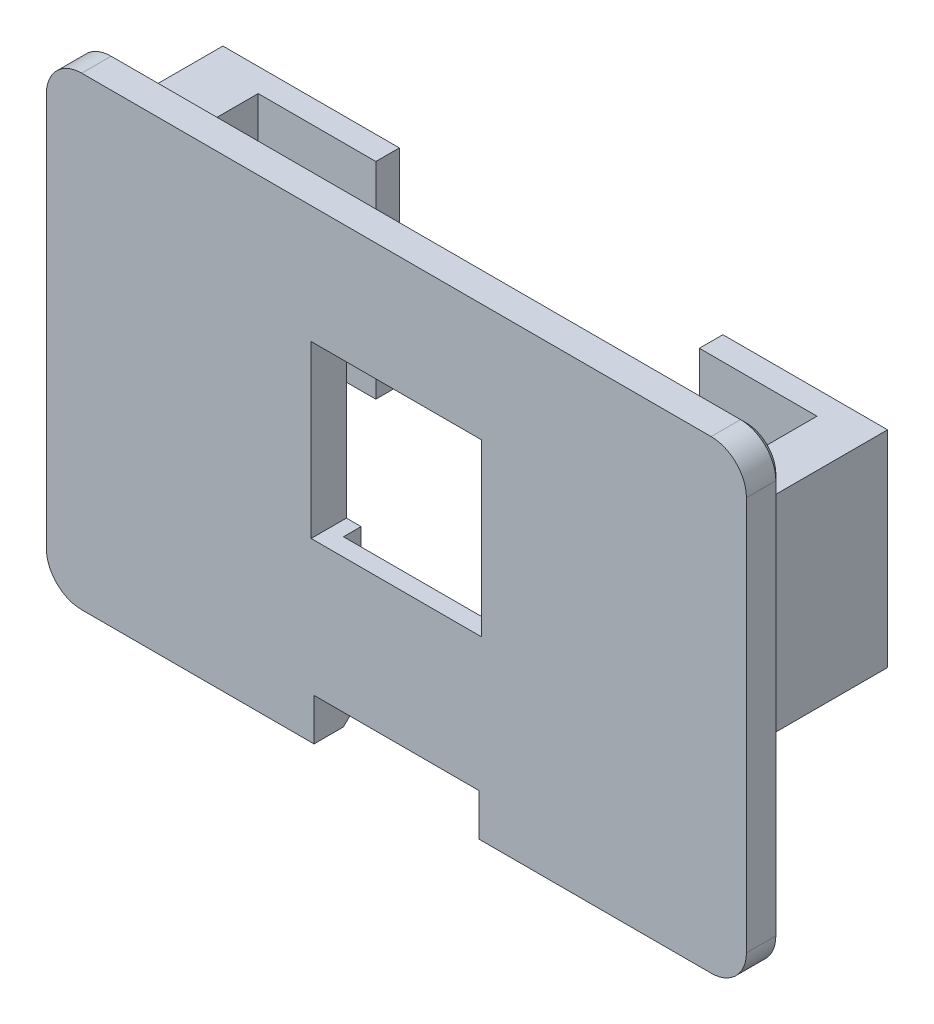
SolidWorks part; units mm, degrees
ref_plane "Front Plane" through (0, 0, 0) normal (0, 0, 1) x (1, 0, 0)
ref_plane "Top Plane" through (0, 0, 0) normal (0, 1, 0) x (1, 0, 0)
ref_plane "Right Plane" through (0, 0, 0) normal (1, 0, 0) x (0, 0, -1)
sketch "Sketch2" plane through (0, 0, 122.2385) normal (0, 0, 1) x (1, 0, 0)
  line L1 (-34.3787, 19.8787) -> (25.1213, 19.8787)
  line L2 (-34.3787, 19.8787) -> (-34.3787, -19.6213)
  line L3 (-34.3787, -19.6213) -> (25.1213, -19.6213)
  line L4 (25.1213, 19.8787) -> (25.1213, -19.6213)
  dimension "D1" = 59.5
  dimension "D2" = 39.5
extrude "Boss-Extrude1" add sketch "Sketch2" along normal blind 3
fillet "Fillet1" radius 3 4 edges at (-34.3787, 19.8787, 123.7385) (25.1213, 19.8787, 123.7385) (25.1213, -19.6213, 123.7385) (-34.3787, -19.6213, 123.7385)
fillet "Chamfer1" radius 0.5 8 edges at (-4.6287, -19.6213, 122.2385) (-34.3787, 0.1287, 122.2385) (-4.6287, 19.8787, 122.2385) (25.1213, 0.1287, 122.2385) (24.2426, -18.7426, 122.2385) (-33.5, -18.7426, 122.2385) (-33.5, 19, 122.2385) (24.2426, 19, 122.2385) profile chamfer
sketch "Sketch3" plane through (0, 0, 122.2385) normal (0, 0, -1) x (-1, 0, 0)
  line L0 (-22.1213, 19.8787) -> (31.3787, 19.8787) construction
  line L7 (-23.6213, 14.3787) -> (-9.6213, 14.3787)
  line L9 (-23.6213, 14.3787) -> (-23.6213, -3.1213)
  line L11 (-23.6213, -3.1213) -> (-9.6213, -3.1213)
  line L17 (-9.6213, 14.3787) -> (-9.6213, -3.1213)
  line L19 (17.8787, 14.3787) -> (32.8787, 14.3787)
  line L20 (17.8787, 14.3787) -> (17.8787, -3.1213)
  line L21 (17.8787, -3.1213) -> (32.8787, -3.1213)
  line L22 (32.8787, 14.3787) -> (32.8787, -3.1213)
  line L23 (-25.1213, -16.6213) -> (-25.1213, 16.8787) construction
  line L24 (34.3787, 16.8787) -> (34.3787, -16.6213) construction
  dimension "D1" = 14
  dimension "D2" = 5.5
  dimension "D3" = 1.5
  dimension "D4" = 1.5
  dimension "D5" = 15
  dimension "D6" = 17.5
  dimension "D7" = 27.5
extrude "Boss-Extrude2" add sketch "Sketch3" along normal blind 10.5
sketch "Sketch4" plane through (0, 0, 122.2385) normal (0, 0, -1) x (-1, 0, 0)
  line L0 (31.3787, -19.6213) -> (-22.1213, -19.6213) construction
  line L1 (-2.3713, -16.0442) -> (11.6287, -16.0442)
  line L2 (-2.3713, -16.0442) -> (-2.3713, -19.6213)
  line L3 (-2.3713, -19.6213) -> (11.6287, -19.6213)
  line L4 (11.6287, -16.0442) -> (11.6287, -19.6213)
  line L6 (-22.1213, 19.8787) -> (31.3787, 19.8787) construction
  line L7 (-2.6213, 9.8787) -> (11.8787, 9.8787)
  line L8 (-2.6213, 9.8787) -> (-2.6213, -4.6213)
  line L9 (-2.6213, -4.6213) -> (11.8787, -4.6213)
  line L10 (11.8787, 9.8787) -> (11.8787, -4.6213)
  point P7 (4.6287, -19.6213)
  point P9 (4.6287, -16.0442)
  point P15 (4.6287, 19.8787)
  point P16 (4.6287, 9.8787)
  dimension "D1" = 14
  dimension "D2" = 10
  dimension "D3" = 14.5
  dimension "D4" = 14.5
extrude "Cut-Extrude1" cut sketch "Sketch4" against normal up to next
sketch "Sketch5" plane through (0, 0, 122.2385) normal (0, 0, -1) x (-1, 0, 0)
  line L0 (11.6287, -16.0442) -> (-2.3713, -16.0442) construction
  line L1 (-1.3713, -1.0442) -> (10.6287, -1.0442)
  line L2 (-1.3713, -1.0442) -> (-1.3713, -16.0442)
  line L3 (-1.3713, -16.0442) -> (10.6287, -16.0442)
  line L4 (10.6287, -1.0442) -> (10.6287, -16.0442)
  point P6 (4.6287, -16.0442)
  point P7 (4.6287, -16.0442)
  dimension "D1" = 12
  dimension "D2" = 15
extrude "Cut-Extrude2" cut sketch "Sketch5" against normal blind 1.5
sketch "Sketch6" plane through (9.6213, 0, 0) normal (-1, 0, 0) x (0, 0, 1)
  line L0 (111.7385, -3.1213) -> (122.2385, -3.1213) construction
  line L1 (113.7385, 14.3787) -> (120.7385, 14.3787)
  line L2 (113.7385, 14.3787) -> (113.7385, -3.1213)
  line L3 (113.7385, -3.1213) -> (120.7385, -3.1213)
  line L4 (120.7385, 14.3787) -> (120.7385, -3.1213)
  line L10 (111.7385, 14.3787) -> (122.2385, 14.3787) construction
  line L11 (111.7385, -3.1213) -> (111.7385, 14.3787) construction
  dimension "D1" = 7
  dimension "D2" = 2
extrude "Cut-Extrude3" cut sketch "Sketch6" against normal blind 10
sketch "Sketch7" plane through (-17.8787, 0, 0) normal (1, 0, 0) x (0, 0, -1)
  line L0 (-111.7385, 14.3787) -> (-122.2385, 14.3787) construction
  line L1 (-120.7385, 14.3787) -> (-113.7385, 14.3787)
  line L2 (-120.7385, 14.3787) -> (-120.7385, -3.1213)
  line L3 (-120.7385, -3.1213) -> (-113.7385, -3.1213)
  line L4 (-113.7385, 14.3787) -> (-113.7385, -3.1213)
  line L5 (-111.7385, -3.1213) -> (-122.2385, -3.1213) construction
  line L6 (-111.7385, 14.3787) -> (-111.7385, -3.1213) construction
  dimension "D1" = 7
  dimension "D2" = 2
extrude "Cut-Extrude4" cut sketch "Sketch7" against normal blind 10 contours L4 L3 L2 L1
